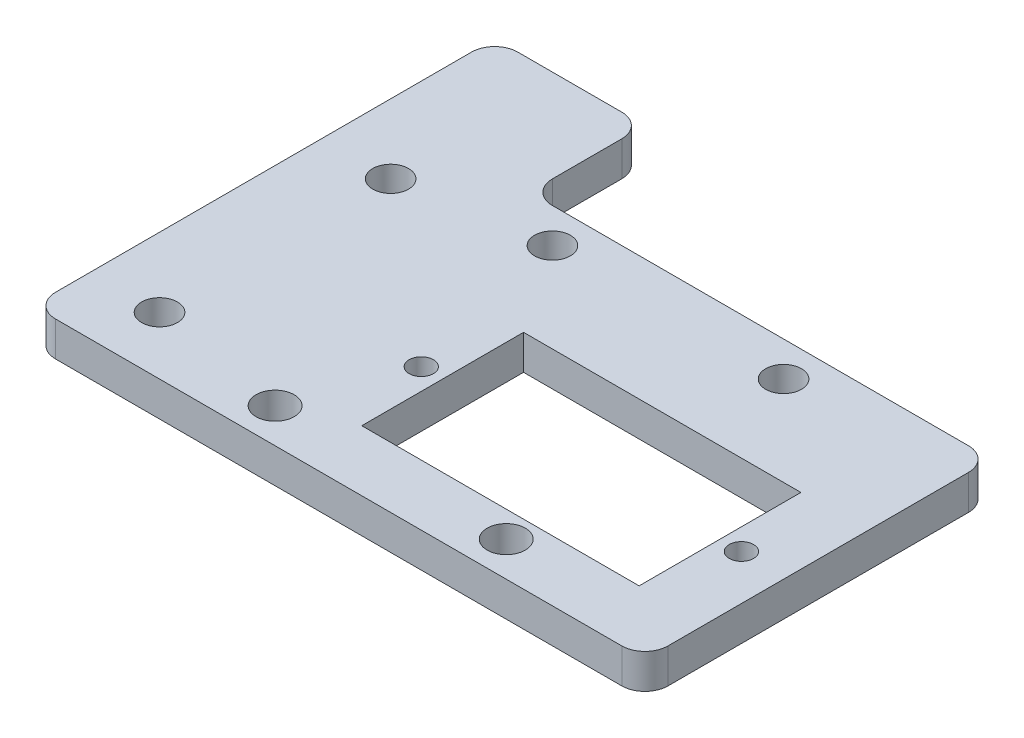
SolidWorks part; units mm, degrees
ref_plane "前视基准面" through (0, 0, 0) normal (0, 0, 1) x (1, 0, 0)
ref_plane "上视基准面" through (0, 0, 0) normal (0, 1, 0) x (1, 0, 0)
ref_plane "右视基准面" through (0, 0, 0) normal (1, 0, 0) x (0, 0, -1)
sketch "草图1" plane through (0, 0, 0) normal (0, 1, 0) x (1, 0, 0)
  line L0 (0, 20) -> (0, -20) construction
  line L1 (-26.5, 20) -> (26.5, 20)
  line L2 (-26.5, 20) -> (-26.5, -20)
  line L3 (-26.5, -20) -> (26.5, -20)
  line L4 (26.5, 20) -> (26.5, -20)
  line L5 (-26.5, 20) -> (26.5, -20) construction
  line L6 (-26.5, -20) -> (26.5, 20) construction
  point P0 (0, 0)
  dimension "D1" = 40
  dimension "D2" = 53
extrude "凸台-拉伸1" add sketch "草图1" along normal blind 3
ref_plane "基准面1" through (0, 0, 0) normal (0, -1, 0) x (-1, 0, 0)
ref_plane "基准面2" through (0, 0, 0) normal (0, -1, 0) x (-1, 0, 0)
sketch "草图2" plane through (0, 0, 0) normal (0, -1, 0) x (-1, 0, 0)
  line L0 (20.5, -20) -> (20.5, -15) construction
  line L1 (26.5, -20) -> (-26.5, -20) construction
  line L2 (20.5, -15) -> (20.5, 5) construction
  line L3 (26.5, 20) -> (26.5, -20) construction
  circle A0 centre (20.5, -15) radius 1.55
  circle A1 centre (20.5, 5) radius 1.55
  dimension "D1" = 3.1
  dimension "D2" = 3.1
  dimension "D3" = 6
  dimension "D4" = 5
  dimension "D5" = 20
extrude "切除-拉伸1" cut sketch "草图2" against normal blind 10
sketch "草图4" plane through (0, 3, 0) normal (0, 1, 0) x (1, 0, 0)
  line L0 (-26.5, 20) -> (-26.5, -20) construction
  line L1 (-26.5, -20) -> (26.5, -20) construction
  line L2 (26.5, -20) -> (26.5, 20) construction
  line L3 (26.5, 20) -> (-26.5, 20) construction
  circle A0 centre (-8.5, -17) radius 1.65
  circle A1 centre (11.5, -17) radius 1.65
  circle A2 centre (-0.5, 17) radius 1.65
  circle A3 centre (19.5, 17) radius 1.65
  dimension "D1" = 3.3
  dimension "D2" = 3.3
  dimension "D3" = 3.3
  dimension "D4" = 3.3
  dimension "D6" = 20
  dimension "D7" = 3
  dimension "D8" = 7
  dimension "D9" = 20
  dimension "D10" = 3
  dimension "D5" = 18
extrude "切除-拉伸2" cut sketch "草图4" against normal blind 10
ref_plane "基准面3" through (0, 3, 0) normal (0, 1, 0) x (1, 0, 0)
sketch "草图5" plane through (0, 3, 0) normal (0, 1, 0) x (1, 0, 0)
  circle A0 centre (22.6, -7.75) radius 1.05
  circle A1 centre (-5.1, -7.75) radius 1.05
  dimension "D1" = 2.1
  dimension "D2" = 2.1
extrude "切除-拉伸3" cut sketch "草图5" against normal blind 10
ref_plane "基准面4" through (0, 0, 0) normal (0, -1, 0) x (-1, 0, 0)
sketch "草图6" plane through (0, 0, 0) normal (0, -1, 0) x (-1, 0, 0)
  line L1 (-20.25, -1.5) -> (2.75, -1.5)
  line L2 (-20.25, -1.5) -> (-20.25, -14)
  line L3 (-20.25, -14) -> (2.75, -14)
  line L4 (2.75, -1.5) -> (2.75, -14)
extrude "切除-拉伸4" cut sketch "草图6" against normal blind 10
sketch "草图7" plane through (0, 0, 0) normal (0, -1, 0) x (-1, 0, 0)
  line L0 (-20.25, -1.5) -> (2.75, -14) construction
  line L2 (-20.75, -0.75) -> (3.25, -0.75)
  line L3 (-20.75, -0.75) -> (-20.75, -14.75)
  line L4 (-20.75, -14.75) -> (3.25, -14.75)
  line L5 (3.25, -0.75) -> (3.25, -14.75)
  line L6 (-20.75, -0.75) -> (3.25, -14.75) construction
  line L7 (-20.75, -14.75) -> (3.25, -0.75) construction
  point P4 (-8.75, -7.75)
  dimension "D1" = 14
  dimension "D2" = 24
extrude "切除-拉伸5" cut sketch "草图7" against normal blind 10
sketch "草图8" plane through (0, 0, 0) normal (0, -1, 0) x (-1, 0, 0)
  line L1 (-26.5, 20) -> (13.5, 20)
  line L2 (-26.5, 20) -> (-26.5, 10)
  line L3 (-26.5, 10) -> (13.5, 10)
  line L4 (13.5, 20) -> (13.5, 10)
  dimension "D1" = 40
  dimension "D2" = 10
extrude "切除-拉伸6" cut sketch "草图8" against normal blind 10
sketch "草图9" plane through (0, 0, 0) normal (0, -1, 0) x (-1, 0, 0)
  line L0 (-26.5, 10) -> (13.5, 10) construction
  line L1 (-26.5, -20) -> (-26.5, 10) construction
  circle A0 centre (-11.5, 7) radius 1.55
  circle A1 centre (8.5, 7) radius 1.55
  dimension "D1" = 20
  dimension "D2" = 3
  dimension "D3" = 3
  dimension "D4" = 3.1
  dimension "D5" = 3.1
  dimension "D6" = 15
extrude "切除-拉伸7" cut sketch "草图9" against normal blind 10
fillet "圆角1" radius 2 6 edges at (-26.5, 1.5, 20) (26.5, 1.5, 20) (26.5, 1.5, -10) (-13.5, 1.5, -10) (-13.5, 1.5, -20) (-26.5, 1.5, -20)
